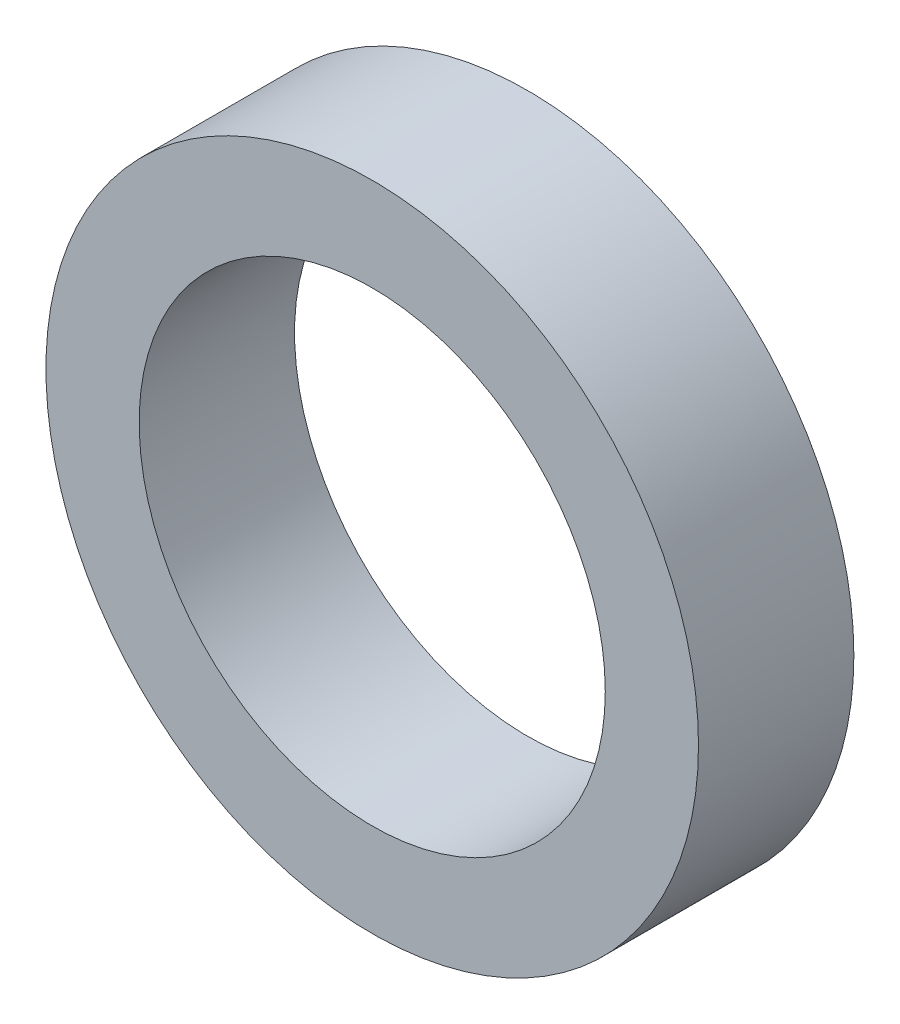
SolidWorks part; units mm, degrees
ref_plane "前视基准面" through (0, 0, 0) normal (0, 0, 1) x (1, 0, 0)
ref_plane "上视基准面" through (0, 0, 0) normal (0, 1, 0) x (1, 0, 0)
ref_plane "右视基准面" through (0, 0, 0) normal (1, 0, 0) x (0, 0, -1)
other "Configuration Table"
sketch "草图1" plane through (0, 0, 0) normal (0, 0, 1) x (1, 0, 0)
  circle A0 centre (0, 0) radius 10.5
  circle A1 centre (0, 0) radius 7.5
extrude "凸台-拉伸1" add sketch "草图1" along normal blind 5
